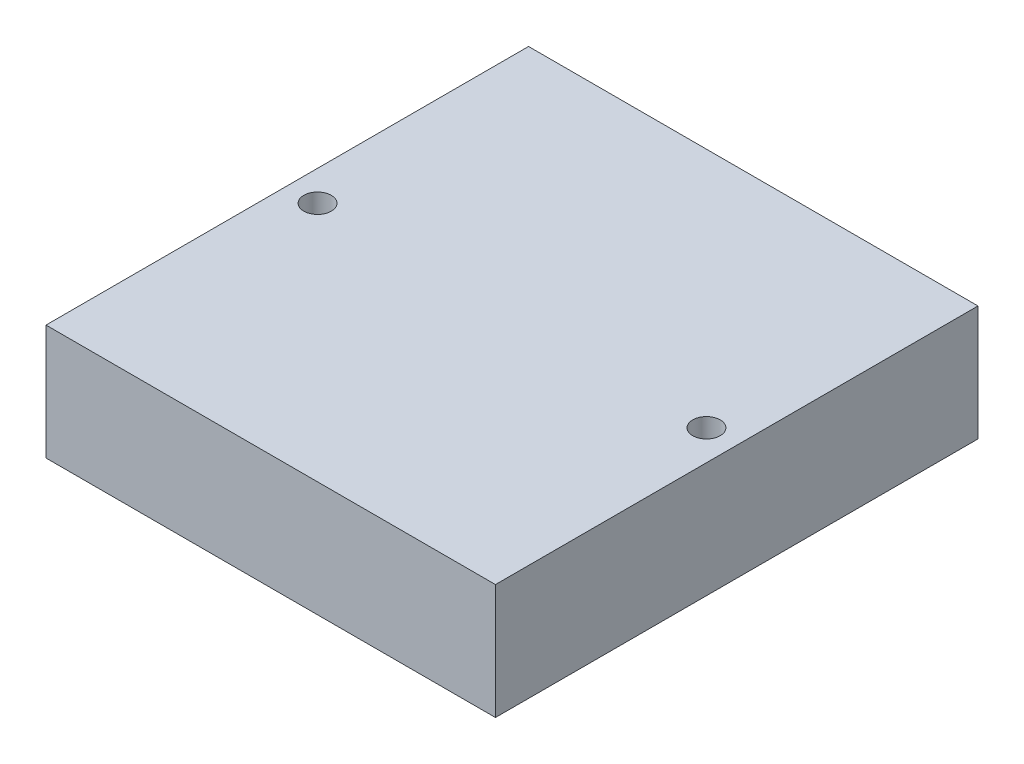
SolidWorks part; units mm, degrees
ref_plane "Front Plane" through (0, 0, 0) normal (0, 0, 1) x (1, 0, 0)
ref_plane "Top Plane" through (0, 0, 0) normal (0, 1, 0) x (1, 0, 0)
ref_plane "Right Plane" through (0, 0, 0) normal (1, 0, 0) x (0, 0, -1)
sketch "Sketch1" plane through (0, 0, 0) normal (0, 1, 0) x (1, 0, 0)
  line L1 (-28.585, -30.69) -> (28.585, -30.69)
  line L2 (-28.585, -30.69) -> (-28.585, 30.69)
  line L3 (-28.585, 30.69) -> (28.585, 30.69)
  line L4 (28.585, -30.69) -> (28.585, 30.69)
  line L5 (-28.585, -30.69) -> (28.585, 30.69) construction
  line L6 (-28.585, 30.69) -> (28.585, -30.69) construction
  circle A0 centre (-24.735, 0) radius 1.75
  circle A1 centre (24.735, 0) radius 1.75
  point P0 (0, 0)
  dimension "D3" = 3.5
  dimension "D5" = 3.5
  dimension "D1" = 57.17
  dimension "D2" = 61.38
  dimension "D4" = 3.85
  dimension "D6" = 3.85
  dimension "D7" = 49.47
extrude "Boss-Extrude1" add sketch "Sketch1" along normal blind 14.65
